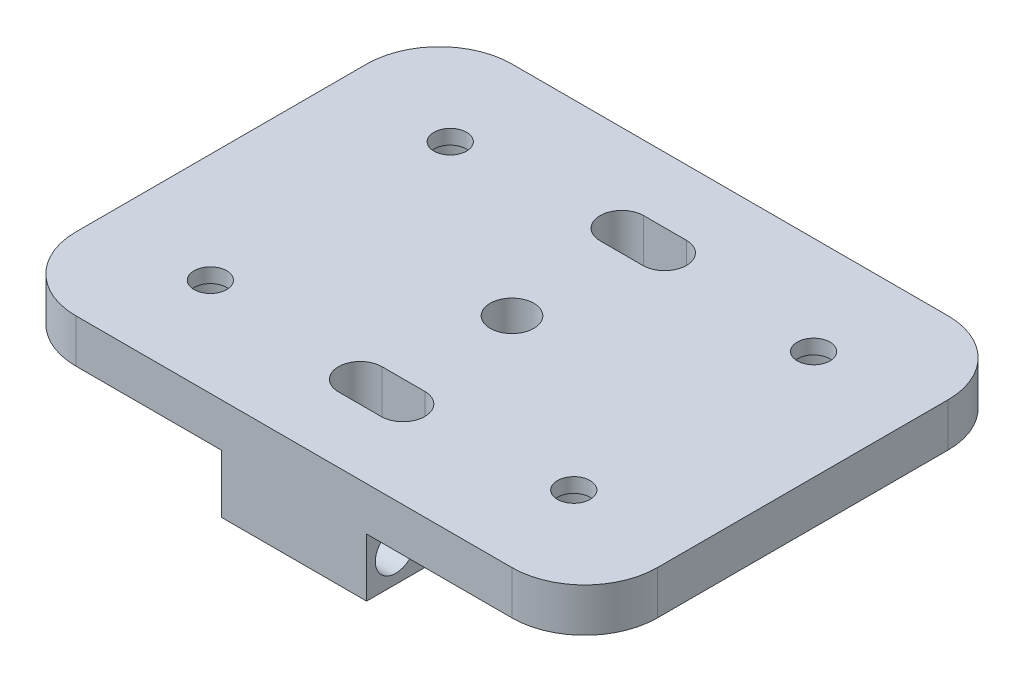
SolidWorks part; units mm, degrees
ref_plane "Plan de face" through (0, 0, 0) normal (0, 0, 1) x (1, 0, 0)
ref_plane "Plan de dessus" through (0, 0, 0) normal (0, 1, 0) x (1, 0, 0)
ref_plane "Plan de droite" through (0, 0, 0) normal (1, 0, 0) x (0, 0, -1)
sketch "Esquisse1" plane through (0, 0, 0) normal (0, 1, 0) x (1, 0, 0)
  line L1 (-30, 30) -> (30, 30)
  line L2 (-40, 20) -> (-40, -20)
  line L3 (-30, -30) -> (30, -30)
  line L4 (40, 20) -> (40, -20)
  line L5 (-29.1047, 30) -> (-9.1047, 30)
  line L7 (-29.1047, -30) -> (-9.1047, -30)
  line L9 (-25, -16.5) -> (25, -16.5) construction
  line L10 (-25, -16.5) -> (-25, 16.5) construction
  line L11 (-25, 16.5) -> (25, 16.5) construction
  line L12 (25, -16.5) -> (25, 16.5) construction
  line L13 (-25, -16.5) -> (25, 16.5) construction
  line L14 (-25, 16.5) -> (25, -16.5) construction
  arc A0 (-30, 30) -> (-40, 20) centre (-30, 20) ccw
  arc A1 (-40, -20) -> (-30, -30) centre (-30, -20) ccw
  arc A2 (30, -30) -> (40, -20) centre (30, -20) ccw
  arc A3 (30, 30) -> (40, 20) centre (30, 20) cw
  circle A8 centre (0, 0) radius 3
  circle A9 centre (-25, -16.5) radius 2.25
  circle A10 centre (25, -16.5) radius 2.25
  circle A11 centre (25, 16.5) radius 2.25
  circle A12 centre (-25, 16.5) radius 2.25
  point P7 (-40, 30)
  point P12 (40, -30)
  point P15 (40, 30)
  dimension "D3" = 10
  dimension "D4" = 6
  dimension "D6" = 33
  dimension "D5" = 50
  dimension "D7" = 4.5
  dimension "D1" = 80
  dimension "D2" = 60
  dimension "D8" = 15
  dimension "D9" = 13.5
extrude "Boss.-Extru.3" add sketch "Esquisse1" along normal blind 6
sketch "Esquisse2" plane through (0, 0, 0) normal (0, -1, 0) x (1, 0, 0)
  line L0 (-30, 30) -> (30, 30) construction
  line L1 (-10, 30) -> (10, 30)
  line L2 (-10, 30) -> (-10, -30)
  line L3 (-10, -30) -> (10, -30)
  line L4 (10, 30) -> (10, -30)
  line L5 (-30, -30) -> (30, -30) construction
  line L6 (-40, -20) -> (-40, 20) construction
  circle A4 centre (0, 0) radius 3 construction
  circle A5 centre (0, 0) radius 3
  dimension "D1" = 20
  dimension "D2" = 30
extrude "Boss.-Extru.4" add sketch "Esquisse2" along normal blind 8
sketch "Esquisse3" plane through (0, 0, 0) normal (0, -1, 0) x (1, 0, 0)
  line L1 (-25, 16.5) -> (25, 16.5) construction
  line L2 (-25, 16.5) -> (-25, -16.5) construction
  line L3 (-25, -16.5) -> (25, -16.5) construction
  line L4 (25, 16.5) -> (25, -16.5) construction
  line L5 (-25, 16.5) -> (25, -16.5) construction
  line L6 (-25, -16.5) -> (25, 16.5) construction
  circle A4 centre (-25, 16.5) radius 4
  circle A5 centre (25, 16.5) radius 4
  circle A6 centre (25, -16.5) radius 4
  circle A7 centre (-25, -16.5) radius 4
  point P0 (0, 0)
  dimension "D1" = 8
extrude "Enlèv. mat.-Extru.2" cut sketch "Esquisse3" against normal blind 4
sketch "Esquisse7" plane through (-10, 0, 0) normal (-1, 0, 0) x (0, 0, 1)
  line L0 (26, -3.8774) -> (-26, -3.8774) construction
  line L1 (30, -8) -> (30, 0) construction
  line L3 (-30, -8) -> (-30, 0) construction
  line L4 (30, -8) -> (-30, -8) construction
  circle A2 centre (26, -3.8774) radius 2.8
  circle A3 centre (-26, -3.8774) radius 2.8
  dimension "D1" = 5.6
  dimension "D2" = 4
  dimension "D3" = 4.1226
  dimension "D4" = 4
extrude "Enlèv. mat.-Extru.8" cut sketch "Esquisse7" against normal blind 8.1
sketch "Esquisse8" plane through (0, -8, 0) normal (0, -1, 0) x (1, 0, 0)
  line L0 (-2.8795, 18) -> (3, 18) construction
  line L1 (-2.8795, 21) -> (3, 21)
  line L2 (-2.8795, 15) -> (3, 15)
  line L3 (-2.8795, -18) -> (3, -18) construction
  line L4 (-2.8795, -15) -> (3, -15)
  line L5 (-2.8795, -21) -> (3, -21)
  line L6 (10, 30) -> (-10, 30) construction
  line L7 (-10, -30) -> (10, -30) construction
  line L9 (10, -30) -> (10, 30) construction
  line L10 (-10, 30) -> (-10, -30) construction
  arc A0 (-2.8795, 21) -> (-2.8795, 15) centre (-2.8795, 18) ccw
  arc A1 (3, 15) -> (3, 21) centre (3, 18) ccw
  arc A2 (-2.8795, -15) -> (-2.8795, -21) centre (-2.8795, -18) ccw
  arc A3 (3, -21) -> (3, -15) centre (3, -18) ccw
  point P2 (0.0602, 18)
  point P7 (0.0602, -18)
  dimension "D1" = 12
  dimension "D3" = 7
  dimension "D4" = 7
  dimension "D6" = 7.1205
  dimension "D2" = 12
  dimension "D5" = 6
extrude "Enlèv. mat.-Extru.9" cut sketch "Esquisse8" against normal through all
sketch "Esquisse9" plane through (10, 0, 0) normal (1, 0, 0) x (0, 0, -1)
  line L0 (-30, -8) -> (-30, 0) construction
  line L1 (30, -8) -> (30, 0) construction
  line L3 (-26, -3.88) -> (26, -3.88) construction
  line L5 (30, -8) -> (-30, -8) construction
  circle A0 centre (-26, -3.88) radius 2.8
  circle A1 centre (26, -3.88) radius 2.8
  dimension "D1" = 5.6
  dimension "D2" = 4
  dimension "D3" = 4
  dimension "D4" = 4.12
  dimension "D5" = 4.12
extrude "Enlèv. mat.-Extru.10" cut sketch "Esquisse9" against normal blind 8.1
